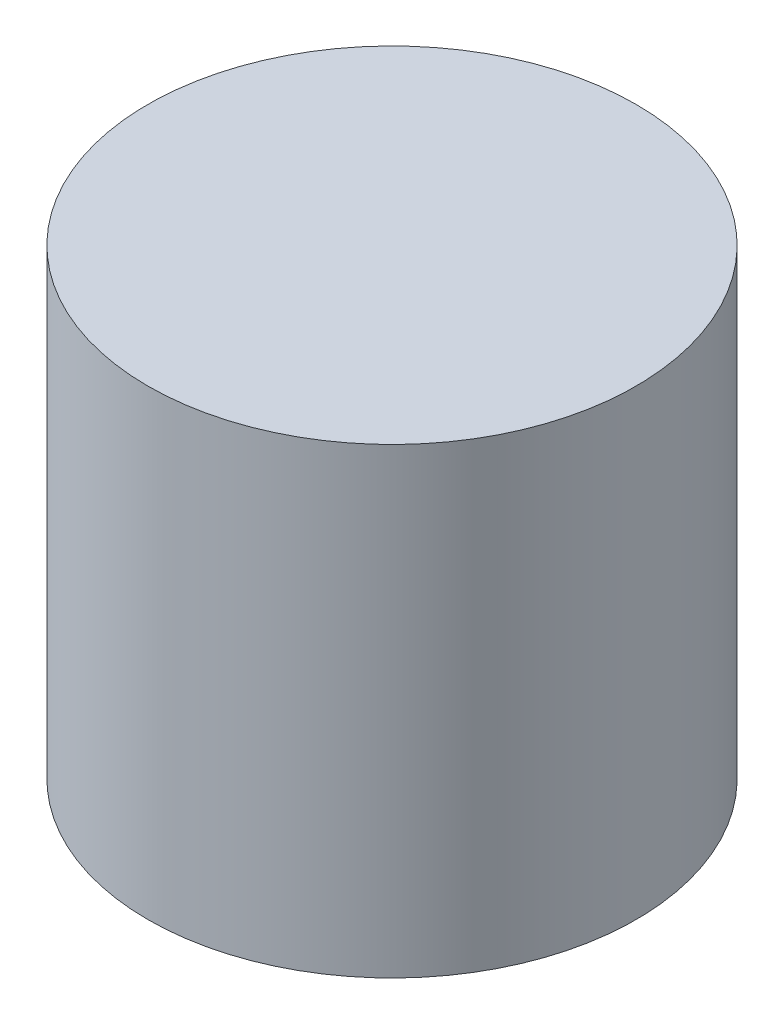
SolidWorks part; units mm, degrees
ref_plane "Front" through (0, 0, 0) normal (0, 0, 1) x (1, 0, 0)
ref_plane "Top" through (0, 0, 0) normal (0, 1, 0) x (1, 0, 0)
ref_plane "Right" through (0, 0, 0) normal (1, 0, 0) x (0, 0, -1)
sketch "Sketch1" plane through (0, 0, 0) normal (0, 1, 0) x (1, 0, 0)
  circle A0 centre (0, 0) radius 37.5
  dimension "D1" = 75
extrude "Boss-Extrude1" add sketch "Sketch1" along normal blind 71
ref_plane "Plane1" through (0, -40, 0) normal (0, -1, 0) x (-1, 0, 0)
